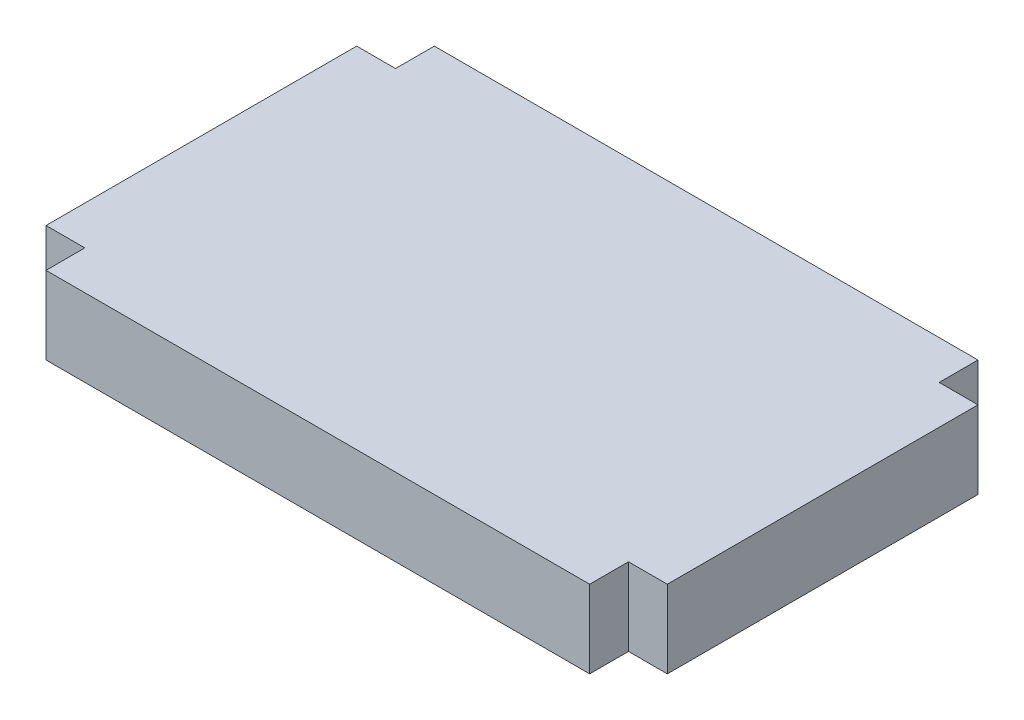
SolidWorks part; units mm, degrees
ref_plane "Front Plane" through (0, 0, 0) normal (0, 0, 1) x (1, 0, 0)
ref_plane "Top Plane" through (0, 0, 0) normal (0, 1, 0) x (1, 0, 0)
ref_plane "Right Plane" through (0, 0, 0) normal (1, 0, 0) x (0, 0, -1)
sketch "Sketch2" plane through (0, 0, 0) normal (0, 1, 0) x (1, 0, 0)
  line L0 (-22.225, 12.7) -> (-22.225, 15.875)
  line L1 (-25.4, 12.7) -> (-22.225, 12.7)
  line L2 (-25.4, 12.7) -> (-25.4, -12.7)
  line L3 (-25.4, -12.7) -> (-22.225, -12.7)
  line L4 (25.4, 12.7) -> (25.4, -12.7)
  line L5 (-25.4, 12.7) -> (25.4, -12.7) construction
  line L6 (-25.4, -12.7) -> (25.4, 12.7) construction
  line L7 (-22.225, 15.875) -> (22.225, 15.875)
  line L8 (22.225, 15.875) -> (22.225, 12.7)
  line L9 (0, -17.1577) -> (0, 22.8776) construction
  line L10 (22.225, 12.7) -> (25.4, 12.7)
  line L11 (-18.7096, 0) -> (22.3816, 0) construction
  line L12 (22.225, -15.875) -> (22.225, -12.7)
  line L13 (-22.225, -15.875) -> (22.225, -15.875)
  line L14 (-22.225, -12.7) -> (-22.225, -15.875)
  line L15 (22.225, -12.7) -> (25.4, -12.7)
  point P0 (0, 0)
  point P12 (0, 15.875)
  dimension "D1" = 25.4
  dimension "D2" = 50.8
  dimension "D3" = 3.175
  dimension "D4" = 44.45
extrude "Boss-Extrude1" add sketch "Sketch2" along normal blind 6.35
